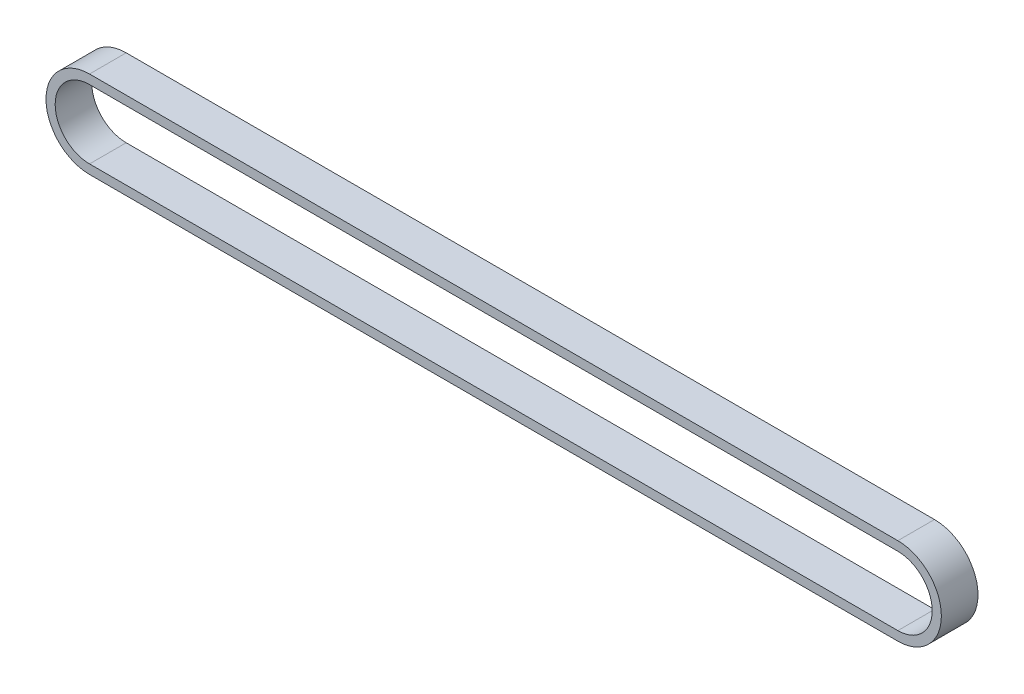
SolidWorks part; units mm, degrees
ref_plane "Front Plane" through (0, 0, 0) normal (0, 0, 1) x (1, 0, 0)
ref_plane "Top Plane" through (0, 0, 0) normal (0, 1, 0) x (1, 0, 0)
ref_plane "Right Plane" through (0, 0, 0) normal (1, 0, 0) x (0, 0, -1)
sketch "Sketch1" plane through (0, 0, 0) normal (0, 0, 1) x (1, 0, 0)
  line L0 (-112.0382, 0) -> (112.0382, 0) construction
  line L1 (-112.0382, 9.525) -> (112.0382, 9.525)
  line L2 (-112.0382, -9.525) -> (112.0382, -9.525)
  line L3 (-112.0382, 12.065) -> (112.0382, 12.065)
  line L4 (-112.0382, -12.065) -> (112.0382, -12.065)
  arc A0 (-112.0382, 9.525) -> (-112.0382, -9.525) centre (-112.0382, 0) ccw
  arc A1 (112.0382, -9.525) -> (112.0382, 9.525) centre (112.0382, 0) ccw
  arc A2 (112.0382, -12.065) -> (112.0382, 12.065) centre (112.0382, 0) ccw
  arc A3 (-112.0382, 12.065) -> (-112.0382, -12.065) centre (-112.0382, 0) ccw
  point P3 (0, 0)
  dimension "D1" = 19.05
  dimension "D2" = 224.0763
  dimension "D3" = 2.54
extrude "Boss-Extrude1" add sketch "Sketch1" along normal blind 10.16
